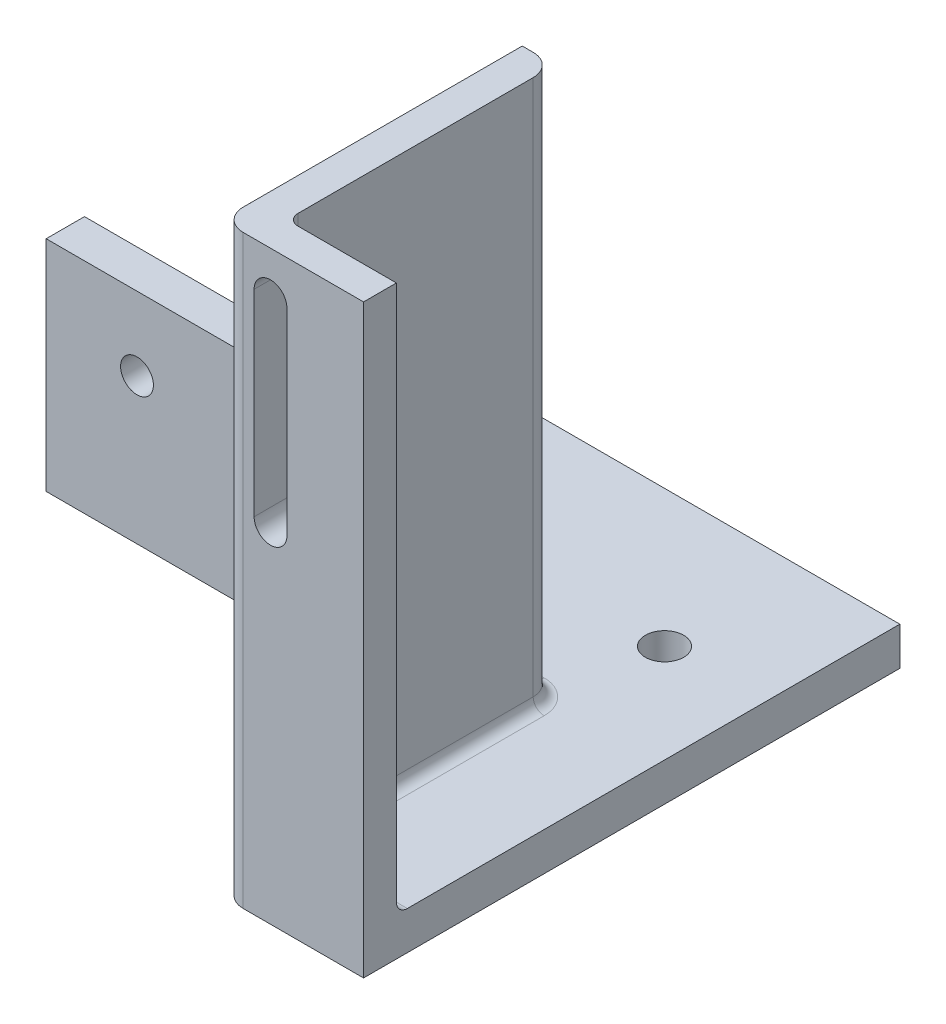
SolidWorks part; units mm, degrees
ref_plane "Front Plane" through (0, 0, 0) normal (0, 0, 1) x (1, 0, 0)
ref_plane "Top Plane" through (0, 0, 0) normal (0, 1, 0) x (1, 0, 0)
ref_plane "Right Plane" through (0, 0, 0) normal (1, 0, 0) x (0, 0, -1)
sketch "Sketch3" plane through (0, 0, 0) normal (1, 0, 0) x (0, 0, -1)
  line L0 (0, 0) -> (0, 20)
  line L1 (0, 20) -> (3.5, 20)
  line L2 (3.5, 20) -> (3.5, 3.5)
  line L3 (3.5, 3.5) -> (25, 3.5)
  line L4 (25, 3.5) -> (25, 0)
  line L5 (25, 0) -> (0, 0)
  dimension "D1" = 3.5
  dimension "D2" = 3.5
  dimension "D3" = 25
  dimension "D4" = 20
extrude "Boss-Extrude2" add sketch "Sketch3" along normal blind 40
sketch "Sketch4" plane through (0, 0, 0) normal (0, 0, 1) x (1, 0, 0)
  line L0 (40, 20) -> (0, 20) construction
  line L5 (23.848, 17.9375) -> (32.865, 17.9375)
  line L6 (23.848, 17.9375) -> (23.848, 13.3655)
  line L7 (23.848, 13.3655) -> (32.865, 13.3655)
  line L8 (32.865, 17.9375) -> (32.865, 13.3655)
  line L9 (0, 20) -> (0, 0) construction
  line L10 (40, 0) -> (0, 0) construction
  circle A0 centre (8.3, 13.3) radius 1.5
  circle A1 centre (31.7, 6.7) radius 1.5
  dimension "D1" = 3
  dimension "D2" = 3
  dimension "D3" = 9.017
  dimension "D4" = 4.572
  dimension "D5" = 6.7
  dimension "D6" = 8.3
  dimension "D7" = 6.7
  dimension "D8" = 31.7
  dimension "D9" = 23.848
  dimension "D10" = 2.0625
extrude "Cut-Extrude1" cut sketch "Sketch4" against normal through all both and the other way through all
sketch "Sketch5" plane through (40, 0, 0) normal (1, 0, 0) x (0, 0, -1)
  line L0 (25, 3.5) -> (3.5, 3.5) construction
  line L1 (25, 0) -> (-24, 0)
  line L2 (25, 0) -> (25, 3.5)
  line L3 (25, 3.5) -> (3.5, 3.5)
  line L4 (-24, 0) -> (-24, 3.5)
  line L5 (0, 20) -> (0, 0) construction
  line L6 (3.5, 53.5) -> (-24, 53.5)
  line L7 (3.5, 53.5) -> (3.5, 3.5)
  line L9 (-24, 53.5) -> (-24, 3.5)
  dimension "D1" = 24
  dimension "D2" = 50
extrude "Boss-Extrude5" add sketch "Sketch5" along normal blind 3
sketch "Sketch7" plane through (43, 0, 0) normal (1, 0, 0) x (0, 0, -1)
  line L0 (-24, 0) -> (25, 0) construction
  line L1 (-24, 53.5) -> (-21, 53.5)
  line L2 (-24, 53.5) -> (-24, 0)
  line L3 (-24, 0) -> (-21, 0)
  line L4 (-21, 53.5) -> (-21, 0)
  line L5 (25, 3.5) -> (3.5, 3.5) construction
  line L6 (25, 0) -> (-21, 0)
  line L7 (25, 0) -> (25, 3.5)
  line L8 (25, 3.5) -> (-21, 3.5)
  line L9 (-21, 0) -> (-21, 3.5)
  line M9 (25, 0) -> (25, 3.5)
  line M10 (25, 3.5) -> (3.5, 3.5)
  line M12 (3.5, 53.5) -> (-24, 53.5)
  line M13 (-24, 53.5) -> (-24, 0)
  line M14 (-24, 0) -> (25, 0)
  dimension "D1" = 3
extrude "Boss-Extrude6" add sketch "Sketch7" along normal blind 10 contours L8 L4 M10 M14 M9 | L4 M12 M13 M14
sketch "Sketch9" plane through (0, 0, 21) normal (0, 0, -1) x (-1, 0, 0)
  line L0 (-44.5, 31.5) -> (-44.5, 49.5) construction
  line L3 (-46, 31.5) -> (-46, 49.5)
  line L4 (-43, 31.5) -> (-43, 49.5)
  line L5 (-43, 53.5) -> (-43, 3.5) construction
  line L6 (-53, 53.5) -> (-43, 53.5) construction
  arc A0 (-46, 31.5) -> (-43, 31.5) centre (-44.5, 31.5) ccw
  arc A1 (-43, 49.5) -> (-46, 49.5) centre (-44.5, 49.5) ccw
  point P2 (-44.5, 40.5)
  dimension "D1" = 3
  dimension "D2" = 4
  dimension "D3" = 18
extrude "Cut-Extrude2" cut sketch "Sketch9" against normal through all both and the other way through all contours L3 A1 L4 A0
fillet "Fillet3" radius 10 1 edges at (40, 20, -1.75)
fillet "Fillet4" radius 1 2 edges at (43, 51.5, 21) (43, 17.5, 21)
fillet "Fillet5" radius 2 3 edges at (43, 28.5, -3.5) (40, 15, 0) (40, 26.75, 24)
fillet "Fillet6" radius 1 5 edges at (48.5, 3.5, 21) (43.2929, 3.5, 20.7071) (43, 3.5, 9.25) (42.4142, 3.5, -2.9142) (20.5, 3.5, -3.5)
sketch "Sketch10" plane through (0, 0, 0) normal (0, -1, 0) x (-1, 0, 0)
  line L0 (-9, 12.5) -> (-44, 12.5) construction
  line L3 (-26.5, 25) -> (-26.5, 0) construction
  line L4 (-53, 25) -> (0, 25) construction
  line L5 (-38, 0) -> (0, 0) construction
  circle A0 centre (-44, 12.5) radius 1.75
  circle A1 centre (-9, 12.5) radius 1.75
  point P0 (-26.5, 12.5)
  point P5 (-26.5, 12.5)
  dimension "D1" = 3.5
  dimension "D2" = 3.5
  dimension "D3" = 35
extrude "Cut-Extrude3" cut sketch "Sketch10" against normal through all both and the other way through all
